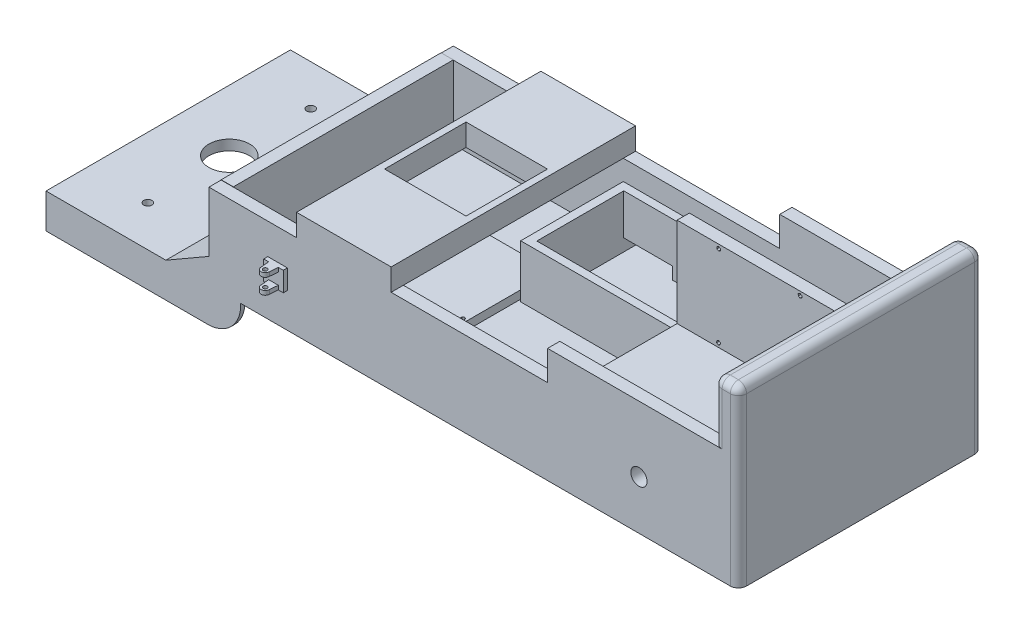
SolidWorks part; units mm, degrees
ref_plane "Front Plane" through (0, 0, 0) normal (0, 0, 1) x (1, 0, 0)
ref_plane "Top Plane" through (0, 0, 0) normal (0, 1, 0) x (1, 0, 0)
ref_plane "Right Plane" through (0, 0, 0) normal (1, 0, 0) x (0, 0, -1)
sketch "Sketch1" plane through (0, 0, 0) normal (0, 1, 0) x (1, 0, 0)
  line L1 (-251.673, 168.8815) -> (398.327, 168.8815)
  line L2 (-251.673, 168.8815) -> (-251.673, -131.1185)
  line L3 (-251.673, -131.1185) -> (398.327, -131.1185)
  line L4 (398.327, 168.8815) -> (398.327, -131.1185)
  dimension "D1" = 650
  dimension "D2" = 300
extrude "Boss-Extrude1" add sketch "Sketch1" along normal blind 14.4342
sketch "Sketch2" plane through (0, 14.4342, 0) normal (0, 1, 0) x (1, 0, 0)
  line L0 (-251.673, -131.1185) -> (398.327, -131.1185) construction
  line L1 (398.327, 168.8815) -> (368.327, 168.8815)
  line L2 (398.327, 168.8815) -> (398.327, -131.1185)
  line L3 (398.327, -131.1185) -> (368.327, -131.1185)
  line L4 (368.327, 168.8815) -> (368.327, -131.1185)
  dimension "D1" = 30
extrude "Boss-Extrude2" add sketch "Sketch2" along normal blind 200
sketch "Sketch3" plane through (0, 0, 131.1185) normal (0, 0, 1) x (1, 0, 0)
  line L1 (368.327, 14.4342) -> (164.0691, 14.4342)
  line L2 (368.327, 14.4342) -> (368.327, 140.576)
  line L3 (368.327, 140.576) -> (164.0691, 140.576)
  line L4 (164.0691, 14.4342) -> (164.0691, 140.576)
extrude "Boss-Extrude3" add sketch "Sketch3" against normal blind 15
sketch "Sketch4" plane through (0, 0, -168.8815) normal (0, 0, -1) x (-1, 0, 0)
  line L1 (-368.327, 14.4342) -> (-164.0691, 14.4342)
  line L2 (-368.327, 14.4342) -> (-368.327, 140.576)
  line L3 (-368.327, 140.576) -> (-164.0691, 140.576)
  line L4 (-164.0691, 14.4342) -> (-164.0691, 140.576)
extrude "Boss-Extrude4" add sketch "Sketch4" against normal blind 15
sketch "Sketch5" plane through (0, 0, 131.1185) normal (0, 0, 1) x (1, 0, 0)
  circle A0 centre (276.1829, 59.9942) radius 10
  dimension "D1" = 20
extrude "Cut-Extrude1" cut sketch "Sketch5" against normal blind 330
sketch "Sketch7" plane through (0, 0, 131.1185) normal (0, 0, 1) x (1, 0, 0)
  line L0 (164.0691, 140.576) -> (164.0691, 14.4342) construction
  line L1 (-251.673, 14.4342) -> (164.0691, 14.4342)
  line L2 (-251.673, 14.4342) -> (-251.673, 104.139)
  line L3 (-251.673, 104.139) -> (164.0691, 104.139)
  line L4 (164.0691, 14.4342) -> (164.0691, 104.139)
extrude "Boss-Extrude5" add sketch "Sketch7" against normal blind 15
sketch "Sketch8" plane through (0, 0, -168.8815) normal (0, 0, -1) x (-1, 0, 0)
  line L1 (251.673, 14.4342) -> (-164.0691, 14.4342)
  line L2 (251.673, 14.4342) -> (251.673, 104.139)
  line L3 (251.673, 104.139) -> (-164.0691, 104.139)
  line L4 (-164.0691, 14.4342) -> (-164.0691, 104.139)
extrude "Boss-Extrude7" add sketch "Sketch8" against normal blind 15
sketch "Sketch9" plane through (0, 0, 131.1185) normal (0, 0, 1) x (1, 0, 0)
  circle A0 centre (-167.3674, 54.3885) radius 10
  dimension "D1" = 20
extrude "Cut-Extrude2" cut sketch "Sketch9" against normal blind 484 contours A0
sketch "Sketch14" plane through (0, -16.7254, 116.1185) normal (0, 0, -1) x (-1, 0, 0)
  line L1 (-368.327, 89.139) -> (-164.0691, 89.139)
  line L2 (-368.327, 89.139) -> (-368.327, 104.139)
  line L3 (-368.327, 104.139) -> (-164.0691, 104.139)
  line L4 (-164.0691, 89.139) -> (-164.0691, 104.139)
  dimension "D1" = 15
extrude "Boss-Extrude8" add sketch "Sketch14" along normal blind 144
sketch "Sketch17" plane through (0, 87.4135, 0) normal (0, 1, 0) x (1, 0, 0)
  line L0 (164.0691, -116.1185) -> (368.327, -116.1185) construction
  line L1 (189.9954, -116.1185) -> (337.1448, -116.1185)
  line L2 (189.9954, -116.1185) -> (189.9954, -96.3856)
  line L3 (189.9954, -96.3856) -> (337.1448, -96.3856)
  line L4 (337.1448, -116.1185) -> (337.1448, -96.3856)
sketch "Sketch19" plane through (0, -16.7254, -27.8815) normal (0, 0, -1) x (-1, 0, 0)
  line L1 (-164.0691, 104.139) -> (-368.327, 104.139)
  line L2 (-164.0691, 104.139) -> (-164.0691, 89.139)
  line L3 (-164.0691, 89.139) -> (-368.327, 89.139)
  line L4 (-368.327, 104.139) -> (-368.327, 89.139)
extrude "Boss-Extrude11" add sketch "Sketch19" along normal blind 15
sketch "Sketch22" plane through (0, 87.4135, 0) normal (0, 1, 0) x (1, 0, 0)
  line L0 (368.327, 168.8815) -> (368.327, -131.1185) construction
  line L1 (164.0691, 42.8815) -> (368.327, 42.8815)
  line L2 (164.0691, 42.8815) -> (164.0691, 27.8815)
  line L3 (164.0691, 27.8815) -> (368.327, 27.8815)
  line L4 (368.327, 42.8815) -> (368.327, 27.8815)
  dimension "D1" = 15
extrude "Boss-Extrude13" add sketch "Sketch22" along normal blind 110
sketch "Sketch23" plane through (0, 0, -27.8815) normal (0, 0, 1) x (1, 0, 0)
  line L7 (214.9865, 189.9053) -> (217.1386, 191.1775)
  line L8 (317.1222, 191.2031) -> (317.1074, 193.703)
  line L9 (317.1074, 193.703) -> (314.935, 194.9402)
  line L10 (314.935, 194.9402) -> (312.7774, 193.6774)
  line L11 (312.7774, 193.6774) -> (312.7921, 191.1775)
  line L12 (312.7921, 191.1775) -> (314.9645, 189.9403)
  line L13 (314.9645, 189.9403) -> (317.1222, 191.2031)
  line L14 (217.1386, 191.1775) -> (217.1128, 193.6774)
  line L15 (217.1128, 193.6774) -> (214.935, 194.905)
  line L16 (214.935, 194.905) -> (212.7829, 193.6328)
  line L17 (212.7829, 193.6328) -> (212.8087, 191.1329)
  line L18 (212.8087, 191.1329) -> (214.9865, 189.9053)
  line L19 (317.0698, 91.203) -> (317.0232, 93.7026)
  line L20 (317.0232, 93.7026) -> (314.8352, 94.912)
  line L21 (314.8352, 94.912) -> (312.6938, 93.6218)
  line L22 (312.6938, 93.6218) -> (312.7404, 91.1222)
  line L23 (312.7404, 91.1222) -> (314.9284, 89.9128)
  line L24 (314.9284, 89.9128) -> (317.0698, 91.203)
  line L25 (217.0013, 91.0877) -> (217.0898, 93.5861)
  line L26 (217.0898, 93.5861) -> (214.9703, 94.912)
  line L27 (214.9703, 94.912) -> (212.7624, 93.7394)
  line L28 (212.7624, 93.7394) -> (212.6739, 91.241)
  line L29 (212.6739, 91.241) -> (214.7933, 89.9151)
  line L30 (214.7933, 89.9151) -> (217.0013, 91.0877)
  circle A0 centre (314.9498, 192.4402) radius 2.1651 construction
  circle A1 centre (214.9607, 192.4051) radius 2.1651 construction
  circle A2 centre (314.8818, 92.4124) radius 2.1651 construction
  circle A3 centre (214.8818, 92.4135) radius 2.1651 construction
  dimension "D2" = 100
  dimension "D3" = 2.5
  dimension "D4" = 102.5
  dimension "D5" = 99.8934
  dimension "D6" = 2.5
  dimension "D7" = 102.3919
  dimension "D8" = 100
  dimension "D9" = 2.5
  dimension "D12" = 2.5
extrude "Cut-Extrude6" cut sketch "Sketch23" against normal blind 23
sketch "Sketch24" plane through (-251.673, 0, 0) normal (-1, 0, 0) x (0, 0, 1)
  line L1 (-168.8815, 0) -> (131.1185, 0)
  line L2 (-168.8815, 0) -> (-168.8815, -42.5)
  line L3 (-168.8815, -42.5) -> (131.1185, -42.5)
  line L4 (131.1185, 0) -> (131.1185, -42.5)
  dimension "D1" = 42.5
extrude "Boss-Extrude14" add sketch "Sketch24" along normal blind 200 separate body contours L2 L1 L4 L3
sketch "Sketch25" plane through (-451.673, 0, 0) normal (-1, 0, 0) x (0, 0, 1)
  line L0 (-168.8815, -42.5) -> (131.1185, -42.5) construction
  line L1 (-163.8815, -42.5) -> (126.1185, -42.5)
  line L2 (-163.8815, -42.5) -> (-163.8815, -12.5588)
  line L3 (-163.8815, -12.5588) -> (126.1185, -12.5588)
  line L4 (126.1185, -42.5) -> (126.1185, -12.5588)
  line L5 (131.1185, 0) -> (131.1185, -42.5) construction
  line L6 (-168.8815, 0) -> (-168.8815, -42.5) construction
  dimension "D1" = 5
  dimension "D2" = 5
sketch "Sketch28" plane through (0, 0, 131.1185) normal (0, 0, 1) x (1, 0, 0)
  line L0 (-251.673, 30.4772) -> (-304.5586, 0)
  line L1 (-251.673, 104.139) -> (-251.673, 0) construction
  line L2 (-451.673, 0) -> (-251.673, 0) construction
  line L3 (-304.5586, 0) -> (-251.673, 0)
  line L4 (-251.673, 0) -> (-251.673, 30.4772)
extrude "Boss-Extrude16" add sketch "Sketch28" against normal blind 300
extrude "Cut-Extrude9" cut sketch "Sketch25" against normal blind 287 contours L3 L4 L1 L2
sketch "Sketch34" plane through (0, 0, 131.1185) normal (0, 0, 1) x (1, 0, 0)
  line L0 (-251.673, -42.5) -> (-251.673, 0)
  line L1 (-251.673, 0) -> (-212.6144, 0)
  line L2 (-251.673, 0) -> (398.327, 0) construction
  arc A0 (-251.673, -42.5) -> (-212.6144, 0) centre (-253.3937, -1.7207) ccw
extrude "Boss-Extrude17" add sketch "Sketch34" against normal blind 5
sketch "Sketch35" plane through (0, 0, -168.8815) normal (0, 0, -1) x (-1, 0, 0)
  line L0 (251.673, 0) -> (251.673, -42.5)
  line L1 (212.6144, 0) -> (251.673, 0)
  arc A0 (251.673, -42.5) -> (212.6144, 0) centre (253.3937, -1.7207) cw
extrude "Boss-Extrude18" add sketch "Sketch35" against normal blind 5
extrude "Cut-Extrude10" cut sketch "Sketch17" against normal blind 40 contours L3 L4 L1 L2
sketch "Sketch39" plane through (0, 0, 0) normal (0, 1, 0) x (1, 0, 0)
  line L0 (-451.673, 168.8815) -> (-304.5586, 168.8815) construction
  line L1 (-451.673, 168.8815) -> (-451.673, -131.1185) construction
  line L2 (-304.5586, 168.8815) -> (-304.5586, -131.1185) construction
  line L3 (-451.673, -131.1185) -> (-304.5586, -131.1185) construction
  circle A0 centre (-376.673, 18.8815) radius 25
  circle A1 centre (-376.673, 118.8815) radius 5
  circle A2 centre (-376.673, -81.1185) radius 5
  dimension "D3" = 10
  dimension "D10" = 10
  dimension "D12" = 50
  dimension "D1" = 150
  dimension "D2" = 100
  dimension "D4" = 75
  dimension "D5" = 72.1145
  dimension "D6" = 75
  dimension "D7" = 100
  dimension "D8" = 50
  dimension "D9" = 50
  dimension "D11" = 72.1145
sketch "Sketch40" plane through (0, 0, -42.8815) normal (0, 0, -1) x (-1, 0, 0)
  line L0 (-368.327, 197.4135) -> (-368.327, 72.4135) construction
  line L1 (-164.0691, 72.4135) -> (-368.327, 72.4135)
  line L2 (-164.0691, 72.4135) -> (-164.0691, 84.4468)
  line L3 (-164.0691, 84.4468) -> (-368.327, 84.4468)
  line L4 (-368.327, 72.4135) -> (-368.327, 84.4468)
extrude "Boss-Extrude19" add sketch "Sketch40" along normal blind 116
sketch "Sketch42" plane through (0, 84.4468, 0) normal (0, 1, 0) x (1, 0, 0)
  line L0 (164.0691, 153.8815) -> (368.327, 153.8815) construction
  line L1 (197.1552, 146.3815) -> (317.1552, 146.3815)
  line L2 (197.1552, 146.3815) -> (197.1552, 51.3815)
  line L3 (197.1552, 51.3815) -> (317.1552, 51.3815)
  line L4 (317.1552, 146.3815) -> (317.1552, 51.3815)
  dimension "D1" = 120
  dimension "D2" = 95
  dimension "D3" = 7.5
extrude "Boss-Extrude21" add sketch "Sketch42" along normal blind 8
sketch "Sketch45" plane through (0, 92.4468, 0) normal (0, 1, 0) x (1, 0, 0)
  line L0 (317.1552, 146.3815) -> (197.1552, 146.3815) construction
  line L1 (200.6552, 143.4815) -> (313.6552, 143.4815)
  line L2 (200.6552, 143.4815) -> (200.6552, 54.4815)
  line L3 (200.6552, 54.4815) -> (313.6552, 54.4815)
  line L4 (313.6552, 143.4815) -> (313.6552, 54.4815)
  line L5 (197.1552, 146.3815) -> (197.1552, 51.3815) construction
  dimension "D1" = 113
  dimension "D2" = 89
  dimension "D3" = 2.9
  dimension "D4" = 3.5
extrude "Cut-Extrude14" cut sketch "Sketch45" against normal blind 6
sketch "Sketch46" plane through (0, 14.4342, 0) normal (0, 1, 0) x (1, 0, 0)
  line L1 (-140.8313, 69.7713) -> (-30.8313, 69.7713)
  line L2 (-140.8313, 69.7713) -> (-140.8313, -40.2287)
  line L3 (-140.8313, -40.2287) -> (-30.8313, -40.2287)
  line L4 (-30.8313, 69.7713) -> (-30.8313, -40.2287)
  dimension "D1" = 110
  dimension "D2" = 110
extrude "Boss-Extrude22" add sketch "Sketch46" along normal blind 10
sketch "Sketch48" plane through (0, 24.4342, 0) normal (0, 1, 0) x (1, 0, 0)
  line L0 (-140.8313, 69.7713) -> (-140.8313, -40.2287) construction
  line L1 (-133.67, 63.5147) -> (-133.6624, 66.0147)
  line L2 (-133.6624, 66.0147) -> (-135.8237, 67.2713)
  line L3 (-135.8237, 67.2713) -> (-137.9925, 66.0278)
  line L4 (-137.9925, 66.0278) -> (-138.0001, 63.5278)
  line L5 (-138.0001, 63.5278) -> (-135.8388, 62.2713)
  line L6 (-135.8388, 62.2713) -> (-133.67, 63.5147)
  line L7 (-30.8313, 69.7713) -> (-140.8313, 69.7713) construction
  line L8 (-33.6624, 66.0147) -> (-35.8237, 67.2713)
  line L9 (-35.8237, 67.2713) -> (-37.9925, 66.0278)
  line L10 (-37.9925, 66.0278) -> (-38.0001, 63.5278)
  line L11 (-38.0001, 63.5278) -> (-35.8388, 62.2713)
  line L12 (-35.8388, 62.2713) -> (-33.67, 63.5147)
  line L13 (-33.67, 63.5147) -> (-33.6624, 66.0147)
  line L14 (-33.6624, -33.9853) -> (-35.8237, -32.7287)
  line L15 (-35.8237, -32.7287) -> (-37.9925, -33.9722)
  line L16 (-37.9925, -33.9722) -> (-38.0001, -36.4722)
  line L17 (-38.0001, -36.4722) -> (-35.8388, -37.7287)
  line L18 (-35.8388, -37.7287) -> (-33.67, -36.4853)
  line L19 (-33.67, -36.4853) -> (-33.6624, -33.9853)
  line L20 (-133.6624, -33.9853) -> (-135.8237, -32.7287)
  line L21 (-135.8237, -32.7287) -> (-137.9925, -33.9722)
  line L22 (-137.9925, -33.9722) -> (-138.0001, -36.4722)
  line L23 (-138.0001, -36.4722) -> (-135.8388, -37.7287)
  line L24 (-135.8388, -37.7287) -> (-133.67, -36.4853)
  line L25 (-133.67, -36.4853) -> (-133.6624, -33.9853)
  circle A0 centre (-135.8313, 64.7713) radius 2.1651 construction
  circle A1 centre (-35.8313, 64.7713) radius 2.1651 construction
  circle A2 centre (-35.8313, -35.2287) radius 2.1651 construction
  circle A3 centre (-135.8313, -35.2287) radius 2.1651 construction
  dimension "D1" = 2.5
  dimension "D2" = 5
  dimension "D3" = 5
  dimension "D4" = 2
  dimension "D5" = 2
extrude "Cut-Extrude18" cut sketch "Sketch48" against normal blind 14.5
extrude "Cut-Extrude19" cut sketch "Sketch39" against normal blind 42
sketch "Sketch50" plane through (0, 14.4342, 0) normal (0, 1, 0) x (1, 0, 0)
  line L0 (164.0691, -116.1185) -> (-251.673, -116.1185) construction
  line L1 (-251.673, 153.8815) -> (-236.673, 153.8815)
  line L2 (-251.673, 153.8815) -> (-251.673, -116.1185)
  line L3 (-251.673, -116.1185) -> (-236.673, -116.1185)
  line L4 (-236.673, 153.8815) -> (-236.673, -116.1185)
  dimension "D1" = 15
extrude "Boss-Extrude30" add sketch "Sketch50" along normal blind 90
sketch "Sketch51" plane through (0, 104.139, 0) normal (0, 1, 0) x (1, 0, 0)
  line L0 (-251.673, 168.8815) -> (164.0691, 168.8815) construction
  line L1 (-144.144, 168.8815) -> (-27.9554, 168.8815)
  line L2 (-144.144, 168.8815) -> (-144.144, -131.1185)
  line L3 (-144.144, -131.1185) -> (-27.9554, -131.1185)
  line L4 (-27.9554, 168.8815) -> (-27.9554, -131.1185)
  line L5 (164.0691, -131.1185) -> (-251.673, -131.1185) construction
extrude "Boss-Extrude33" add sketch "Sketch51" along normal blind 27
sketch "Sketch56" plane through (0, 131.139, 0) normal (0, 1, 0) x (1, 0, 0)
  line L0 (-144.144, 168.8815) -> (-144.144, -131.1185) construction
  line L1 (-136.044, 68.8815) -> (-36.044, 68.8815)
  line L2 (-136.044, 68.8815) -> (-136.044, -31.1185)
  line L3 (-136.044, -31.1185) -> (-36.044, -31.1185)
  line L4 (-36.044, 68.8815) -> (-36.044, -31.1185)
  line L5 (-27.9554, 168.8815) -> (-144.144, 168.8815) construction
  dimension "D1" = 100
  dimension "D2" = 100
  dimension "D3" = 8.1
  dimension "D4" = 100
extrude "Cut-Extrude22" cut sketch "Sketch56" against normal blind 46
sketch "Sketch58" plane through (0, 0, 131.1185) normal (0, 0, 1) x (1, 0, 0)
  line L1 (-179.3674, 66.3885) -> (-155.3674, 66.3885)
  line L2 (-179.3674, 66.3885) -> (-179.3674, 42.3885)
  line L3 (-179.3674, 42.3885) -> (-155.3674, 42.3885)
  line L4 (-155.3674, 66.3885) -> (-155.3674, 42.3885)
  circle A0 centre (-167.3674, 54.3885) radius 10 construction
  dimension "D1" = 24
  dimension "D2" = 24
  dimension "D3" = 24
  dimension "D4" = 12
  dimension "D5" = 12
extrude "Boss-Extrude35" add sketch "Sketch58" along normal blind 5
sketch "Sketch61" plane through (0, 0, -168.8815) normal (0, 0, -1) x (-1, 0, 0)
  line L1 (155.3674, 66.3885) -> (179.3674, 66.3885)
  line L2 (155.3674, 66.3885) -> (155.3674, 42.3885)
  line L3 (155.3674, 42.3885) -> (179.3674, 42.3885)
  line L4 (179.3674, 66.3885) -> (179.3674, 42.3885)
  circle A0 centre (167.3674, 54.3885) radius 10 construction
  dimension "D1" = 24
  dimension "D2" = 24
  dimension "D3" = 12
  dimension "D4" = 12
  dimension "D5" = 12
extrude "Boss-Extrude36" add sketch "Sketch61" along normal blind 5
sketch "Sketch62" plane through (0, 66.3885, 0) normal (0, 1, 0) x (1, 0, 0)
  line L0 (-174.0674, 173.8815) -> (-172.3674, 183.9388)
  line L1 (-179.3674, 173.8815) -> (-155.3674, 173.8815) construction
  line L3 (-162.3674, 183.9388) -> (-160.6674, 173.8815)
  line L4 (-174.0674, 173.8815) -> (-160.6674, 173.8815)
  arc A0 (-172.3674, 183.9388) -> (-162.3674, 183.9388) centre (-167.3674, 183.9388) cw
  dimension "D1" = 10.2
  dimension "D2" = 10.2
  dimension "D3" = 10
  dimension "D4" = 5.3
  dimension "D5" = 5.3
extrude "Boss-Extrude37" add sketch "Sketch62" against normal blind 5
sketch "Sketch63" plane through (0, 42.3885, 0) normal (0, -1, 0) x (1, 0, 0)
  line L0 (-174.0674, -173.8815) -> (-172.3674, -183.9388)
  line L1 (-174.0674, -173.8815) -> (-160.6674, -173.8815)
  line L2 (-160.6674, -173.8815) -> (-162.3674, -183.9388)
  arc A0 (-172.3674, -183.9388) -> (-162.3674, -183.9388) centre (-167.3674, -183.9388) ccw
extrude "Boss-Extrude38" add sketch "Sketch63" against normal blind 5
sketch "Sketch64" plane through (0, 0, 0) normal (0, 1, 0) x (1, 0, 0)
  line L0 (-167.3674, 188.9388) -> (-167.3674, 183.9388) construction
  arc A0 (-162.3674, 183.9388) -> (-172.3674, 183.9388) centre (-167.3674, 183.9388) ccw construction
  circle A1 centre (-167.3674, 183.9388) radius 2.55
  dimension "D1" = 5.1
extrude "Cut-Extrude23" cut sketch "Sketch64" along normal blind 93
sketch "Sketch65" plane through (0, 66.3885, 0) normal (0, 1, 0) x (1, 0, 0)
  line L0 (-173.3174, -136.1185) -> (-172.3924, -146.2765)
  line L1 (-155.3674, -136.1185) -> (-179.3674, -136.1185) construction
  line L3 (-162.3924, -146.2765) -> (-161.4674, -136.1185)
  line L4 (-161.4674, -136.1185) -> (-173.3174, -136.1185)
  arc A0 (-172.3924, -146.2765) -> (-162.3924, -146.2765) centre (-167.3924, -146.2765) ccw
  dimension "D1" = 10
  dimension "D2" = 10.2
  dimension "D3" = 10.2
  dimension "D4" = 6.1
  dimension "D5" = 6.05
extrude "Boss-Extrude39" add sketch "Sketch65" against normal blind 5
sketch "Sketch67" plane through (0, 42.3885, 0) normal (0, -1, 0) x (1, 0, 0)
  line L0 (-173.3174, 136.1185) -> (-172.3924, 146.2765)
  line L2 (-162.3924, 146.2765) -> (-161.4674, 136.1185)
  line L3 (-161.4674, 136.1185) -> (-173.3174, 136.1185)
  arc A0 (-172.3924, 146.2765) -> (-162.3924, 146.2765) centre (-167.3924, 146.2765) cw
sketch "Sketch68" plane through (0, 0, 0) normal (0, 1, 0) x (1, 0, 0)
  line L0 (-167.3924, -156.2765) -> (-167.3924, -146.2765)
  circle A1 centre (-167.3924, -146.2765) radius 2.5363
  point P3 (-167.3924, -151.2765)
  dimension "D1" = 5.0727
extrude "Boss-Extrude41" add sketch "Sketch67" against normal blind 5
extrude "Cut-Extrude25" cut sketch "Sketch68" along normal blind 77 contours A1
sketch "Sketch69" plane through (0, 14.4342, 0) normal (0, 1, 0) x (1, 0, 0)
  line L1 (-27.9554, 153.8815) -> (164.0691, 153.8815)
  line L2 (-27.9554, 153.8815) -> (-27.9554, 27.8815)
  line L3 (-27.9554, 27.8815) -> (164.0691, 27.8815)
  line L4 (164.0691, 153.8815) -> (164.0691, 27.8815)
extrude "Boss-Extrude42" add sketch "Sketch69" along normal blind 65
sketch "Sketch70" plane through (0, 79.4342, 0) normal (0, 1, 0) x (1, 0, 0)
  line L0 (164.0691, 153.8815) -> (-27.9554, 153.8815) construction
  line L1 (-17.783, 144.2315) -> (154.9419, 144.2315)
  line L2 (-17.783, 144.2315) -> (-17.783, 37.5315)
  line L3 (-17.783, 37.5315) -> (154.9419, 37.5315)
  line L4 (154.9419, 144.2315) -> (154.9419, 37.5315)
  line L5 (-27.9554, 27.8815) -> (164.0691, 27.8815) construction
  line L6 (164.0691, 27.8815) -> (164.0691, 153.8815) construction
  line L7 (-27.9554, 153.8815) -> (-27.9554, 27.8815) construction
  dimension "D1" = 9.65
  dimension "D2" = 9.65
  dimension "D3" = 9.1272
  dimension "D4" = 10.1724
extrude "Cut-Extrude26" cut sketch "Sketch70" against normal blind 65
fillet "Fillet1" radius 10 1 edges at (398.327, 214.4342, -18.8815)
fillet "Fillet2" radius 10 3 edges at (378.327, 214.4342, -168.8815) (398.327, 102.2171, -168.8815) (395.398, 211.5053, -168.8815)
fillet "Fillet3" radius 10 3 edges at (378.327, 214.4342, 131.1185) (398.327, 102.2171, 131.1185) (395.398, 211.5053, 131.1185)
fillet "Fillet4" radius 10 5 edges at (368.327, 172.5051, -168.8815) (368.327, 214.4342, -18.8815) (368.327, 211.5053, -165.9525) (368.327, 172.5051, 131.1185) (368.327, 211.5053, 128.1896)
sketch "Sketch72" plane through (0, 0, -144.2315) normal (0, 0, 1) x (1, 0, 0)
  line L1 (-17.783, 14.4342) -> (42.217, 14.4342)
  line L2 (-17.783, 14.4342) -> (-17.783, 29.4342)
  line L3 (-17.783, 29.4342) -> (42.217, 29.4342)
  line L4 (42.217, 14.4342) -> (42.217, 29.4342)
  dimension "D1" = 60
  dimension "D2" = 15
extrude "Cut-Extrude30" cut sketch "Sketch72" against normal blind 29
